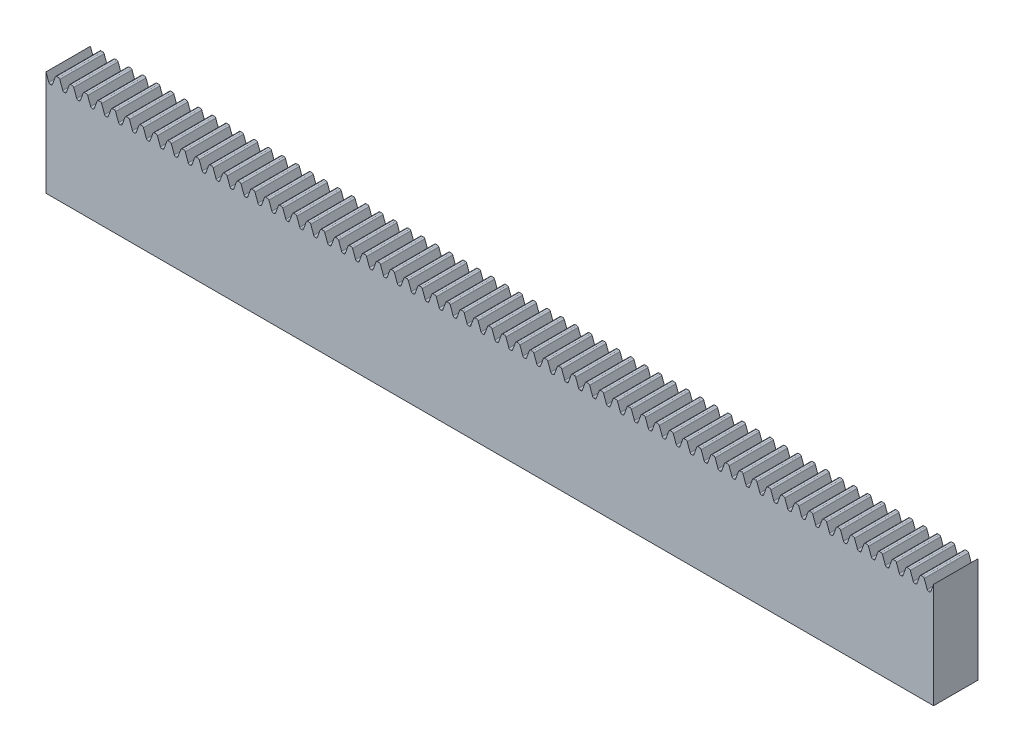
SolidWorks part; units mm, degrees
ref_plane "Front Plane" through (0, 0, 0) normal (0, 0, 1) x (1, 0, 0)
ref_plane "Top Plane" through (0, 0, 0) normal (0, 1, 0) x (1, 0, 0)
ref_plane "Right Plane" through (0, 0, 0) normal (1, 0, 0) x (0, 0, -1)
sketch "Sketch1" plane through (0, 0, 0) normal (0, 0, 1) x (1, 0, 0)
  line L0 (-50, 6) -> (-50, -6) construction
  line L1 (-50, -6) -> (50, -6) construction
  line L2 (50, -6) -> (50, 6) construction
  line L4 (0, 6) -> (0, -6) construction
  line L5 (-50, 5.5) -> (50, 5.5) construction
  line L6 (-48.9054, 6) -> (-48.484, 6) construction
  line L7 (-48.484, 6) -> (-48.0745, 4.875) construction
  line L8 (-48.9054, 6) -> (-49.3149, 4.875) construction
  line L9 (-49.3149, 4.875) -> (-48.0745, 4.875) construction
  line L10 (-48.6947, 6) -> (-48.6947, 4.875) construction
  line L11 (-50, 0) -> (-45.5531, 0) construction
  line L12 (50, 0) -> (45.5531, 0) construction
  point P15 (-47.1239, 6)
  point P16 (-31.5, -6)
  point P17 (-48.302, 5.5)
  point P18 (-49.0874, 5.5)
  point P21 (-0.25, -6)
  dimension "Length" = 100
  dimension "Height" = 12
  dimension "Approximate Number of Teeth" = 63
  dimension "Pressure Angle" = 20
  dimension "Circular Pitch" = 1.5708
  dimension "Addendum" = 0.5
  dimension "Dedendum" = 0.625
  dimension "Circular Tooth Thickness" = 0.7854
  dimension "Module" = 0.5
  dimension "Rack Length" = 97.3894
  dimension "D1" = 3.1416
sketch "Sketch2" plane through (0, 0, 0) normal (1, 0, 0) x (0, 0, -1)
  line L0 (-2.5, 0) -> (2.5, 0) construction
  dimension "Face Width" = 5
sketch "Sketch3" plane through (0, 0, 0) normal (0, 0, 1) x (1, 0, 0)
  line L1 (-50, 6) -> (50, 6)
  line L2 (-50, 6) -> (-50, -6)
  line L3 (-50, -6) -> (50, -6)
  line L4 (50, 6) -> (50, -6)
extrude "Boss-Extrude1" add sketch "Sketch3" against normal up to vertex (2.5 mm away) and the other way up to vertex (2.5 mm away) up to point (0, 0, -2.5) other way up to point (0, 0, 2.5)
sketch "Sketch4" plane through (0, 0, 0) normal (0, 0, 1) x (1, 0, 0)
  line L0 (-48.6947, 6) -> (-47.1239, 6) construction
  line L9 (-47.9093, 6) -> (-47.9093, 4.875)
  line L10 (-47.9093, 4.875) -> (-48.0745, 4.875)
  line L11 (-48.0745, 4.875) -> (-48.484, 6)
  line L12 (-48.484, 6) -> (-47.9093, 6)
  line L13 (-48.9054, 6) -> (-49.3149, 4.875)
  line L14 (-49.3149, 4.875) -> (-49.4801, 4.875)
  line L15 (-49.4801, 4.875) -> (-49.4801, 6)
  line L16 (-49.4801, 6) -> (-48.9054, 6)
  line L17 (50, 6) -> (-50, 6) construction
  line L18 (-48.9054, 6) -> (-48.7879, 6)
  line L19 (-48.6014, 6) -> (-48.484, 6)
  arc A0 (-49.4323, 4.875) -> (-49.2747, 4.9854) centre (-49.4323, 5.0428) ccw
  arc A1 (-48.1147, 4.9854) -> (-47.957, 4.875) centre (-47.957, 5.0428) ccw
  arc A2 (-48.9456, 5.8896) -> (-48.7879, 6) centre (-48.7879, 5.8322) cw
  arc A3 (-48.6014, 6) -> (-48.4438, 5.8896) centre (-48.6014, 5.8322) cw
  dimension "D1" = 0.1678
extrude "Cut-Extrude1" cut sketch "Sketch4" against normal through all both and the other way through all contours L14 A0 L13 L16 L15 | L13 A2 L18 | L19 A3 L11 | L11 A1 L10 L9 L12
pattern_linear "LPattern1" count 64 spacing 1.5708 along (1, 0, 0) count 2 spacing 1.5708 along (-1, 0, 0) of "Cut-Extrude1"
sketch "Drawing Refernce 1" plane through (0, 0, 2.5) normal (0, 0, 1) x (1, 0, 0)
  line L0 (-50, 0) -> (50, 0) construction
  point P6 (-35, 0)
  point P7 (-27.5, 0)
  point P8 (35, 0)
  dimension "D1" = 15
  dimension "D2" = 22.5
  dimension "D3" = 15
equation "\"Diametral Pitch\"= 1 / \"Module\""
equation "\"Pressure Angle\"=20"
equation "\"Dedendum\"= 1.25 / \"Diametral Pitch\""
equation "\"Addendum\"= 1 / \"Diametral Pitch\""
equation "\"WorkingDepth\"= 2 / \"Diametral Pitch\""
equation "\"WholeDepth\"= 2.25 / \"Diametral Pitch\""
equation "\"Clearance\"= 0.25 / \"Diametral Pitch\""
equation "\"ToothThickness\"= ( pi / 2 ) / \"Diametral Pitch\""
equation "\"CircularPitch\"= pi / \"Diametral Pitch\""
equation "\"Fillet\"= \"Clearance\" * cos ( \"Pressure Angle\" ) * tan ( ( 90 + \"Pressure Angle\" ) / 2 )"
equation "\"Module\"= 0.5"
equation "\"Addendum@Sketch1\"=\"Addendum\""
equation "\"Pressure Angle@Sketch1\"=\"Pressure Angle\""
equation "\"Dedendum@Sketch1\"=\"Dedendum\""
equation "\"Circular Pitch@Sketch1\"=\"CircularPitch\""
equation "\"Circular Tooth Thickness@Sketch1\"=\"ToothThickness\""
equation "\"Module@Sketch1\"=\"Module\""
equation "\"Approximate Number of Teeth@Sketch1\" = int ( \"Length@Sketch1\" /  ( 2 * \"Circular Tooth Thickness@Sketch1\" )  ) "
equation "\"Rack Length@Sketch1\" = \"Circular Pitch@Sketch1\" *  ( \"Approximate Number of Teeth@Sketch1\" - 1 ) "
equation "\"D3@LPattern1\"=\"CircularPitch\""
equation "\"D1@LPattern1\"=\"Approximate Number of Teeth@Sketch1\"+1"
equation "\"D1@Sketch1\"=\"Circular Pitch@Sketch1\"*2"
equation "\"D1@Sketch4\"=\"Fillet\""
equation "\"D4@LPattern1\"=\"CircularPitch\""
equation "\"D2@Drawing Refernce 1\"=\"D1@Drawing Refernce 1\"*1.5"
equation "\"D3@Drawing Refernce 1\"=\"D1@Drawing Refernce 1\""
